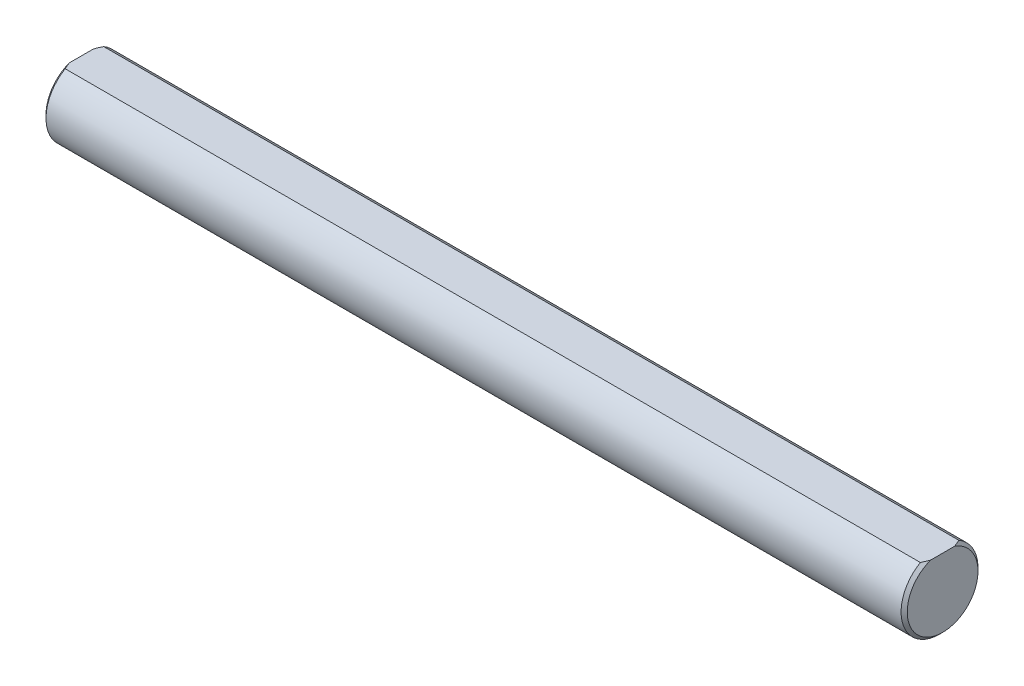
SolidWorks part; units mm, degrees
material "AISI 1045 Steel, cold drawn"
ref_plane "Front Plane" through (0, 0, 0) normal (0, 0, 1) x (1, 0, 0)
ref_plane "Top Plane" through (0, 0, 0) normal (0, 1, 0) x (1, 0, 0)
ref_plane "Right Plane" through (0, 0, 0) normal (1, 0, 0) x (0, 0, -1)
sketch "Sketch1" plane through (0, 0, 0) normal (1, 0, 0) x (0, 0, -1)
  circle A2 centre (0, 0) radius 3.175
  dimension "D1" = 6.35
extrude "Boss-Extrude1" add sketch "Sketch1" along normal blind 71.12
chamfer "Chamfer1" distance 0.254 angle 45 2 edges at (71.12, 0, -3.175) (0, 0, -3.175)
sketch "Sketch2" plane through (71.12, 0, 0) normal (1, 0, 0) x (0, 0, -1)
  line L0 (-1.5875, 2.7496) -> (1.5875, 2.7496)
  circle A0 centre (0, 0) radius 3.175 construction
  arc A1 (1.5875, 2.7496) -> (-1.5875, 2.7496) centre (0, 0) ccw
  dimension "D1" = 3.175
extrude "Cut-Extrude2" cut sketch "Sketch2" against normal through all
